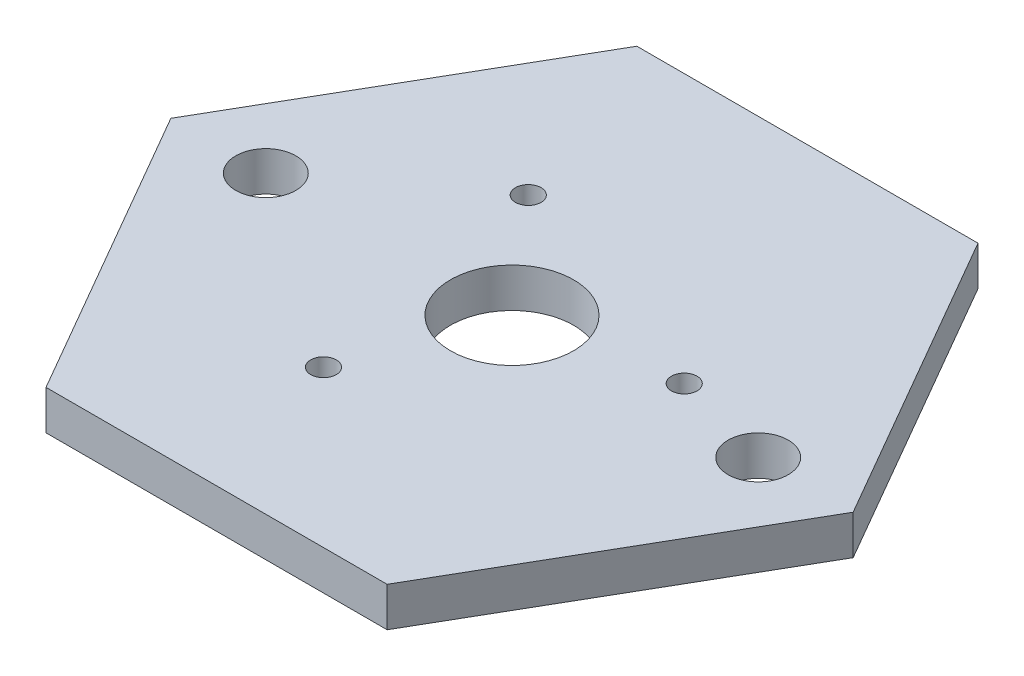
SolidWorks part; units mm, degrees
ref_plane "前视基准面" through (0, 0, 0) normal (0, 0, 1) x (1, 0, 0)
ref_plane "上视基准面" through (0, 0, 0) normal (0, 1, 0) x (1, 0, 0)
ref_plane "右视基准面" through (0, 0, 0) normal (1, 0, 0) x (0, 0, -1)
sketch "草图1" plane through (0, 0, 0) normal (0, 1, 0) x (1, 0, 0)
  line L1 (69.282, 0) -> (34.641, 60)
  line L2 (34.641, 60) -> (-34.641, 60)
  line L3 (-34.641, 60) -> (-69.282, 0)
  line L4 (-69.282, 0) -> (-34.641, -60)
  line L5 (-34.641, -60) -> (34.641, -60)
  line L6 (34.641, -60) -> (69.282, 0)
  circle A0 centre (0, 0) radius 60 construction
  dimension "D1" = 120
extrude "凸台-拉伸1" add sketch "草图1" along normal blind 8
sketch "草图2" plane through (0, 8, 0) normal (0, 1, 0) x (1, 0, 0)
  line L0 (-69.282, 0) -> (69.282, 0) construction
  circle A0 centre (-50, 0) radius 6.1
  circle A1 centre (50, 0) radius 6.1
  dimension "D1" = 12.2
  dimension "D2" = 50
  dimension "D3" = 12.2
  dimension "D4" = 50
extrude "切除-拉伸1" cut sketch "草图2" against normal through all
sketch "草图4" plane through (0, 8, 0) normal (0, 1, 0) x (1, 0, 0)
  circle A0 centre (0, 0) radius 12.5
  dimension "D1" = 25
extrude "切除-拉伸3" cut sketch "草图4" against normal through all
sketch "草图5" plane through (0, 8, 0) normal (0, 1, 0) x (1, 0, 0)
  line L0 (0, 0) -> (0, -60) construction
  line L1 (-34.641, -60) -> (34.641, -60) construction
  line L2 (0, 0) -> (-10, -28.2843) construction
  line L3 (-10, -28.2843) -> (0, -28.2843) construction
  circle A0 centre (-10, -28.2843) radius 2.6
  circle A1 centre (-19.4949, 22.8024) radius 2.6
  circle A2 centre (29.4949, 5.4819) radius 2.6
  point P14 (0, 0)
  dimension "D3" = 5.2
  dimension "D1" = 10
  dimension "D2" = 30
  dimension "D4" = 3
extrude "切除-拉伸4" cut sketch "草图5" against normal through all
sketch "草图6" plane through (0, 0, 0) normal (0, -1, 0) x (1, 0, 0)
  circle A0 centre (-10, 28.2843) radius 5.5
  circle A1 centre (-19.4949, -22.8024) radius 5.5
  circle A2 centre (29.4949, -5.4819) radius 5.5
  dimension "D1" = 11
  dimension "D2" = 11
  dimension "D3" = 11
extrude "切除-拉伸5" cut sketch "草图6" against normal blind 1.5
equation "\"14。1\"=8.26391"
